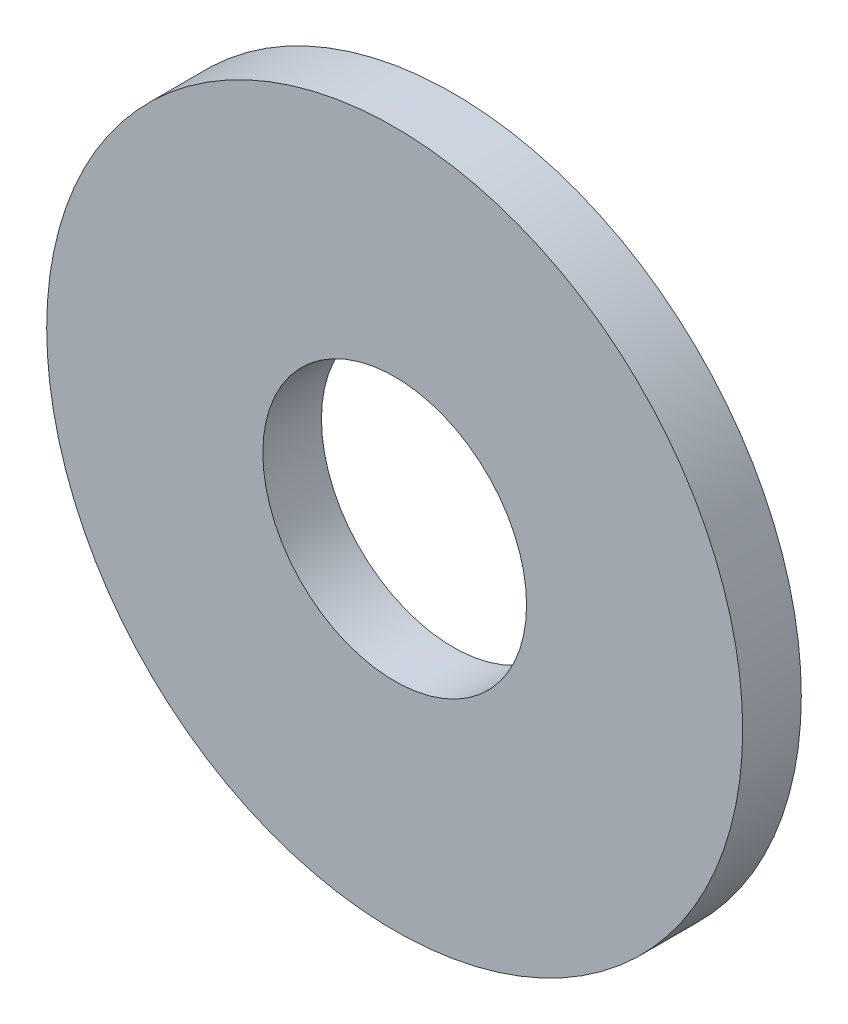
SolidWorks part; units mm, degrees
ref_plane "Front Plane" through (0, 0, 0) normal (0, 0, 1) x (1, 0, 0)
ref_plane "Top Plane" through (0, 0, 0) normal (0, 1, 0) x (1, 0, 0)
ref_plane "Right Plane" through (0, 0, 0) normal (1, 0, 0) x (0, 0, -1)
sketch "Sketch1" plane through (0, 0, 0) normal (1, 0, 0) x (0, 0, -1)
  line L0 (0, 0) -> (3.6005, 0) construction
  line L1 (0, 4.75) -> (0.8, 4.75)
  line L2 (0, 4.75) -> (0, 1.8)
  line L3 (0, 1.8) -> (0.8, 1.8)
  line L4 (0.8, 4.75) -> (0.8, 1.8)
  dimension "D1" = 9.5
  dimension "D2" = 3.6
  dimension "D3" = 0.8
revolve "Revolve1" add sketch "Sketch1" angle 360 about L0
